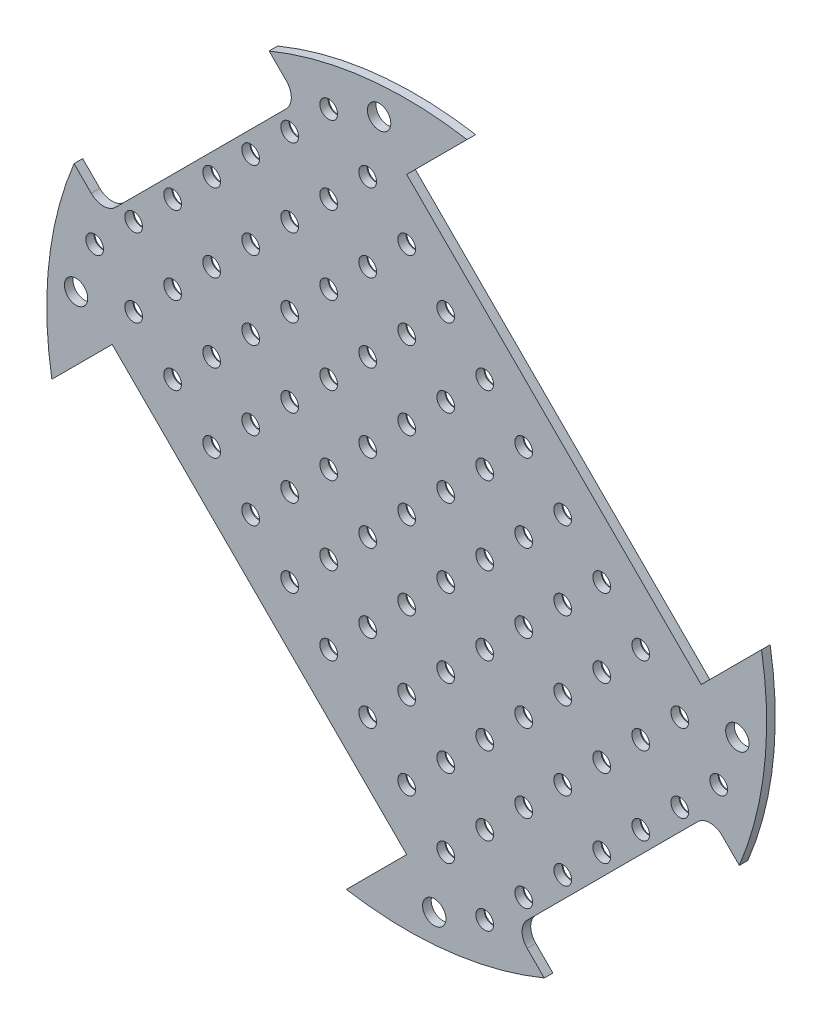
SolidWorks part; units mm, degrees
material "6061-T6 (SS)"
ref_plane "Front Plane" through (0, 0, 0) normal (0, 0, 1) x (1, 0, 0)
ref_plane "Top Plane" through (0, 0, 0) normal (0, 1, 0) x (1, 0, 0)
ref_plane "Right Plane" through (0, 0, 0) normal (1, 0, 0) x (0, 0, -1)
sketch "Sketch1" plane through (0, 0, 0) normal (0, 0, 1) x (1, 0, 0)
  circle A0 centre (0, 0) radius 66.294
  dimension "D1" = 132.588
extrude "Extrude1" add sketch "Sketch1" along normal blind 1.5875
sketch "Sketch2" plane through (0, 0, 1.5875) normal (0, 0, 1) x (1, 0, 0)
  line L0 (0, 0) -> (0, 66.294) construction
  line L1 (0, 66.294) -> (0, -66.294) construction
  line L2 (0, -66.294) -> (0, 0) construction
  line L3 (0, 0) -> (66.294, 0) construction
  line L4 (66.294, 0) -> (-66.294, 0) construction
  circle A0 centre (0, 0) radius 66.294 construction
sketch "Sketch6" plane through (0, 0, 1.5875) normal (0, 0, 1) x (1, 0, 0)
  line L0 (0, 66.294) -> (0, 51.308) construction
  line L1 (0, 0) -> (0, 66.294) construction
  dimension "D1" = 14.986
sketch "Sketch3" plane through (0, 0, 1.5875) normal (0, 0, 1) x (1, 0, 0)
  line L0 (0, 0) -> (12.1169, 0) construction
  line L1 (0, 0) -> (66.294, 0) construction
  line L2 (0, 54.2407) -> (54.2407, 0)
  line L3 (0, 0) -> (0, 54.2407) construction
  line L4 (0, 0) -> (0, 12.1169) construction
  line L5 (0, 0) -> (0, 66.294) construction
  line L6 (12.1803, 66.421) -> (66.421, 66.421)
  line L7 (0, 0) -> (54.2407, 0) construction
  line L8 (0, 54.2407) -> (12.1803, 66.421)
  line L9 (66.421, 66.421) -> (66.421, 12.1803)
  line L10 (54.2407, 0) -> (66.421, 12.1803)
  dimension "D1" = 76.708
extrude "Extrude2" cut sketch "Sketch3" against normal through all
pattern_circular "CirPattern1" count 2 over 180 about axis through (0, 0, 0) along (0, 0, 1) of "Extrude2"
sketch "Sketch11" plane through (0, 0, 0) normal (0, 0, -1) x (-1, 0, 0)
  line L0 (-66.294, 0) -> (-55.8604, 0) construction
  line L1 (-55.8604, 0) -> (-55.8604, -19.9394) construction
  line L2 (-55.8604, -19.9394) -> (-69.0112, -33.0902)
  line L3 (-69.0112, -33.0902) -> (-33.0902, -69.0112)
  line L4 (-33.0902, -69.0112) -> (-19.9394, -55.8604)
  line L5 (-19.9394, -55.8604) -> (-55.8604, -19.9394)
  line L6 (0, -66.294) -> (0, -55.8604) construction
  line L7 (0, -55.8604) -> (-19.9394, -55.8604) construction
  line L8 (0, 54.2407) -> (-54.2407, 0) construction
  arc A0 (-65.3556, 11.1149) -> (11.1149, -65.3556) centre (0, 0) ccw construction
  dimension "D1" = 50.8
extrude "Extrude3" cut sketch "Sketch11" against normal through all
sketch "Sketch8" plane through (0, 0, 1.5875) normal (0, 0, 1) x (1, 0, 0)
  line L0 (0, 62.484) -> (0, 60.8965) construction
  line L1 (0, 66.294) -> (0, 51.308) construction
  line L2 (0, 60.8965) -> (-5.08, 60.8965) construction
  line L3 (62.484, 0) -> (60.8965, 0) construction
  line L4 (60.8965, 0) -> (60.8965, -5.08) construction
  line L5 (0, -56.1023) -> (0, 56.1023) construction
  line L6 (0, 66.294) -> (0, 62.484) construction
  line L7 (0, 62.484) -> (3.048, 62.484) construction
  line L8 (66.294, 0) -> (62.484, 0) construction
  line L9 (62.484, 0) -> (62.484, 3.048) construction
  circle A0 centre (0, 0) radius 66.294 construction
  arc A1 (61.2602, -25.3392) -> (65.3556, 11.1149) centre (0, 0) ccw construction
  dimension "D1" = 5.3975
  dimension "D2" = 5.08
  dimension "D3" = 3.81
  dimension "D4" = 3.048
  dimension "D5" = 5.3975
  dimension "D6" = 3.048
  dimension "D7" = 5.08
sketch "Sketch23" plane through (0, 0, 1.5875) normal (0, 0, 1) x (1, 0, 0)
  line L0 (61.2602, -25.3392) -> (56.7701, -20.8491) construction
  line L2 (55.8604, -19.9394) -> (61.2602, -25.3392) construction
  line L3 (56.7701, -20.8491) -> (59.2846, -18.3346) construction
  line L4 (25.3392, -61.2602) -> (20.8491, -56.7701) construction
  line L5 (25.3392, -61.2602) -> (19.9394, -55.8604) construction
  line L6 (20.8491, -56.7701) -> (18.3346, -59.2846) construction
  line L7 (37.8999, -37.8999) -> (35.2058, -35.2058) construction
  line L8 (19.9394, -55.8604) -> (55.8604, -19.9394) construction
  line L9 (19.9394, -55.8604) -> (55.8604, -19.9394) construction
  dimension "D1" = 6.35
  dimension "D2" = 3.556
  dimension "D3" = 3.81
pattern_circular "CirPattern4" count 2 over 180 about axis through (0, 0, 0) along (0, 0, 1) of "Extrude3"
hole_wizard "#6 Clearance Hole1" positions "3DSketch3" profile "Sketch10" hole size "#6" standard "Ansi Inch" end condition through all
sketch3d "3DSketch3"
  point P0 (-5.08, 60.8965, 1.5875)
  point P3 (60.8965, -5.08, 1.5875)
sketch "Sketch10" plane through (-5.08, 60.8965, 1.5875) normal (1, 0, 0) x (0, -1, 0)
  line L0 (0, 0) -> (0, 1.5875)
  line L1 (0, 1.5875) -> (2.1526, 1.5875)
  line L2 (2.1526, 1.5875) -> (2.1526, 0)
  line L5 (2.1526, 0) -> (0, 0)
  line L11 (0, -6.35) -> (0, 107.95) construction
  dimension "Thru Hole Dia." = 4.3053
  dimension "Thru Hole Depth" = 1.5875
pattern_circular "CirPattern3" count 2 over 180 about axis through (0, 0, 0) along (0, 0, 1) of "#6 Clearance Hole1"
sketch "Sketch32" plane through (0, 0, 1.5875) normal (0, 0, 1) x (1, 0, 0)
  point P0 (0, 0)
hole_wizard "#4 Clearance Hole4" positions "Sketch34" profile "Sketch33" hole size "#4" standard "Ansi Inch"
sketch "Sketch34" plane through (0, 0, 1.5875) normal (0, 0, 1) x (1, 0, 0)
  point P1 (0, 0)
sketch "Sketch33" plane through (0, 0, 1.5875) normal (1, 0, 0) x (0, -1, 0)
  line L0 (0, 0) -> (0, 2.5046)
  line L1 (0, 2.5046) -> (1.6319, 1.524)
  line L2 (1.6319, 1.524) -> (1.6319, 0)
  line L5 (1.6319, 0) -> (0, 0)
  line L10 (0, 2.5046) -> (-1.6319, 1.524) construction
  line L11 (0, -6.35) -> (0, 107.95) construction
  dimension "Hole Dia." = 3.2639
  dimension "Hole Depth" = 1.524
  dimension "Drill Angle" = 118
pattern_linear "LPattern1" count 4 spacing 10.16 along (-0.7071, -0.7071, 0) count 4 spacing 10.16 along (0.7071, 0.7071, 0) of "#4 Clearance Hole4"
pattern_linear "LPattern2" count 6 spacing 10.16 along (0.7071, -0.7071, 0) count 6 spacing 10.16 along (-0.7071, 0.7071, 0) of "LPattern1", "#4 Clearance Hole4"
fillet "Fillet1" radius 3.175 4 edges at (-55.8604, 19.9394, 0.7937) (-19.9394, 55.8604, 0.7937) (55.8604, -19.9394, 0.7937) (19.9394, -55.8604, 0.7937)
sketch "Sketch28" plane through (0, 0, 1.5875) normal (0, 0, 1) x (1, 0, 0)
  line L0 (0, -54.2407) -> (-54.2407, 0) construction
  line L1 (0, 54.2407) -> (54.2407, 0) construction
  point P0 (-27.1204, -27.1204)
  point P1 (27.1204, 27.1204)
